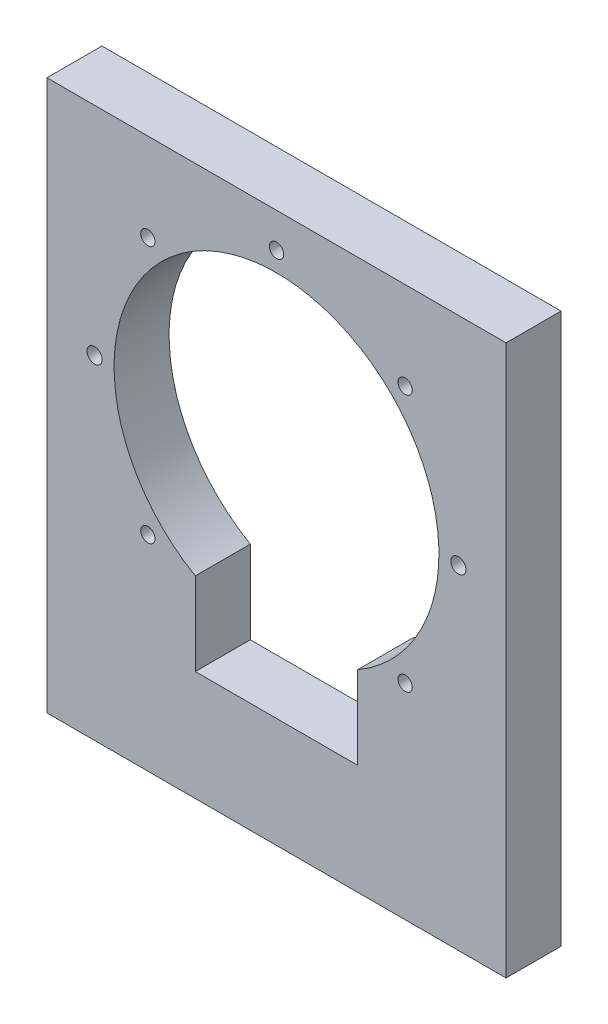
SolidWorks part; units mm, degrees
material "1060 Alloy"
ref_plane "Front Plane" through (0, 0, 0) normal (0, 0, 1) x (1, 0, 0)
ref_plane "Top Plane" through (0, 0, 0) normal (0, 1, 0) x (1, 0, 0)
ref_plane "Right Plane" through (0, 0, 0) normal (1, 0, 0) x (0, 0, -1)
sketch "Sketch1" plane through (0, 0, 0) normal (0, 0, 1) x (1, 0, 0)
  line L1 (0, 76.2) -> (106, 76.2)
  line L5 (0, 76.2) -> (0, -50.8)
  line L6 (0, -50.8) -> (106, -50.8)
  line L7 (0, 76.2) -> (0, -50.8) construction
  line L8 (53, 26.2) -> (53, -11.3) construction
  line L9 (53, 26.2) -> (34.25, -6.276) construction
  line L10 (53, 26.2) -> (71.75, -6.276) construction
  line L11 (34.25, -6.276) -> (34.25, -25.4)
  line L12 (71.75, -6.276) -> (71.75, -25.4)
  line L13 (71.75, -25.4) -> (34.25, -25.4)
  line L21 (106, 76.2) -> (106, -50.8)
  arc A6 (71.75, -6.276) -> (34.25, -6.276) centre (53, 26.2) ccw
  circle A7 centre (53, 26.2) radius 42 construction
  circle A9 centre (82.6985, 55.8985) radius 1.6497
  circle A10 centre (95, 26.2) radius 1.746
  circle A11 centre (82.6985, -3.4985) radius 1.6497
  circle A13 centre (23.3015, -3.4985) radius 1.6497
  circle A14 centre (11, 26.2) radius 1.746
  circle A15 centre (23.3015, 55.8985) radius 1.6497
  circle A33 centre (53, 68.2) radius 1.6497
  point P0 (0, 0)
  point P6 (53, 26.2)
  point P32 (53, 26.2)
  point P38 (53, 26.2)
  dimension "D6" = 75
  dimension "D7" = 84
  dimension "D8" = 3.2995
  dimension "D3" = 3.492
  dimension "D9" = 3.492
  dimension "D4" = 53
  dimension "D5" = 50
  dimension "D10" = 30
  dimension "D11" = 30
  dimension "D2" = 25.4
  dimension "D12" = 127
  dimension "D13" = 106
extrude "Boss-Extrude1" add sketch "Sketch1" along normal blind 12.7
equation "\"bplate_length\"= 24in"
equation "\"bplate_height\"= 6in"
equation "\"bplate_thickness\"= 0.5in"
equation "\"motor_diameter\"= 96 / 25.4in"
equation "\"motor_clearance\"= 5 / 25.4in"
equation "\"motor_mount_hole_pattern_dia\"= 84 / 25.4in"
equation "\"motor_mount_hole_dia\"= 4 / 25.4in"
equation "\"motor_cx\"= \"motor_clearance\" + \"motor_diameter\" / 2in"
equation "\"motor_cy_top\"= \"motor_mount_hole_pattern_dia\" / 2 + \"motor_mount_hole_dia\" * 2in"
equation "\"motor_driver_cover_dia\"= 75 / 25.4in"
equation "\"D4@Sketch1\"=\"motor_cx\""
equation "\"motor_driver_cutout_clearance\"= 60deg"
equation "\"wire_cutout_clearance\"= 2in"
equation "\"connector_plate_thickness\"= 1in"
equation "\"connector_plate_hole_diameter\"= 0.5in"
equation "\"connector_plate_hole_depth\"= 1in"
equation "\"coonector_first_hole_offset\"= 1.6in"
equation "\"D6@Sketch1\"=\"motor_driver_cover_dia\""
equation "\"D7@Sketch1\"=\"motor_mount_hole_pattern_dia\""
equation "\"D8@Sketch1\"=0.1299"
equation "\"D3@Sketch1\"=\"motor_mount_hole_dia\" - 0.02"
